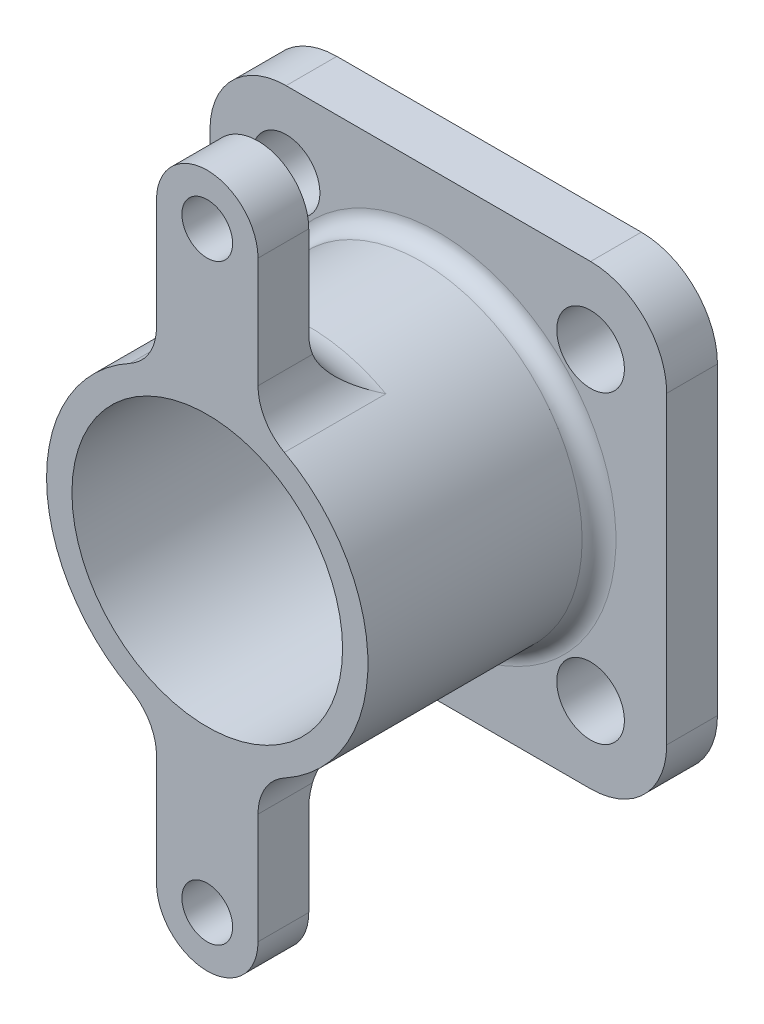
SolidWorks part; units mm, degrees
material "ABS"
ref_plane "Front Plane" through (0, 0, 0) normal (0, 0, 1) x (1, 0, 0)
ref_plane "Top Plane" through (0, 0, 0) normal (0, 1, 0) x (1, 0, 0)
ref_plane "Right Plane" through (0, 0, 0) normal (1, 0, 0) x (0, 0, -1)
sketch "Sketch1" plane through (0, 0, 0) normal (0, 0, 1) x (1, 0, 0)
  line L1 (-16, -13.5) -> (2, -13.5)
  line L2 (-20.5, -9) -> (-20.5, 9)
  line L3 (-16, 13.5) -> (2, 13.5)
  line L4 (6.5, -9) -> (6.5, 9)
  line L5 (-20.5, -13.5) -> (6.5, 13.5) construction
  line L6 (-20.5, 13.5) -> (6.5, -13.5) construction
  line L7 (-16, -9) -> (2, -9) construction
  line L12 (-16, -9) -> (-16, 9) construction
  line L13 (-16, 9) -> (2, 9) construction
  line L14 (2, -9) -> (2, 9) construction
  line L15 (-16, -9) -> (2, 9) construction
  line L16 (-16, 9) -> (2, -9) construction
  arc A4 (2, 13.5) -> (6.5, 9) centre (2, 9) cw
  arc A5 (2, -13.5) -> (6.5, -9) centre (2, -9) ccw
  arc A6 (-16, -13.5) -> (-20.5, -9) centre (-16, -9) cw
  arc A7 (-20.5, 9) -> (-16, 13.5) centre (-16, 9) cw
  circle A16 centre (-7, 0) radius 8
  circle A17 centre (-16, 9) radius 2
  circle A18 centre (2, 9) radius 2
  circle A19 centre (2, -9) radius 2
  circle A20 centre (-16, -9) radius 2
  dimension "D2" = 16
  dimension "D4" = 4.5
  dimension "D6" = 4
  dimension "D1" = 27
  dimension "D3" = 27
  dimension "D5" = 18
extrude "Boss-Extrude1" add sketch "Sketch1" along normal blind 3
sketch "Sketch2" plane through (0, 0, 0) normal (0, 0, 1) x (1, 0, 0)
  circle A1 centre (-7, 0) radius 8
  circle A2 centre (-7, 0) radius 8 construction
  circle A6 centre (-7, 0) radius 9.5
  dimension "D1" = 1.5
extrude "Boss-Extrude2" add sketch "Sketch2" along normal blind 16.66
sketch "Sketch3" plane through (0, 0, 16.66) normal (0, 0, 1) x (1, 0, 0)
  line L0 (-7, 0) -> (17.5448, 0) construction
  line L2 (-10, 17.5) -> (-10, 9.0139)
  line L3 (-4, 17.5) -> (-4, 9.0139)
  line L4 (-7, 0) -> (-7, 6.9852) construction
  line L6 (-4, -17.5) -> (-4, -9.0139)
  line L7 (-10, -17.5) -> (-10, -9.0139)
  circle A4 centre (-7, 0) radius 9.5 construction
  circle A8 centre (-7, 17.5) radius 1.5
  circle A9 centre (-7, 17.5) radius 3
  arc A10 (-10, 9.0139) -> (-4, 9.0139) centre (-7, 0) cw
  arc A11 (-10, -9.0139) -> (-4, -9.0139) centre (-7, 0) ccw
  circle A12 centre (-7, -17.5) radius 3
  circle A13 centre (-7, -17.5) radius 1.5
  dimension "D1" = 3
  dimension "D2" = 6
  dimension "D3" = 35
extrude "Boss-Extrude3" add sketch "Sketch3" against normal blind 3
fillet "Fillet1" radius 3 6 edges at (-7, 9.5, 13.66) (-7, -9.5, 13.66) (-10, -9.0139, 15.16) (-4, -9.0139, 15.16) (-10, 9.0139, 15.16) (-4, 9.0139, 15.16)
fillet "Fillet2" radius 1 1 edges at (-16.5, 0, 3)
